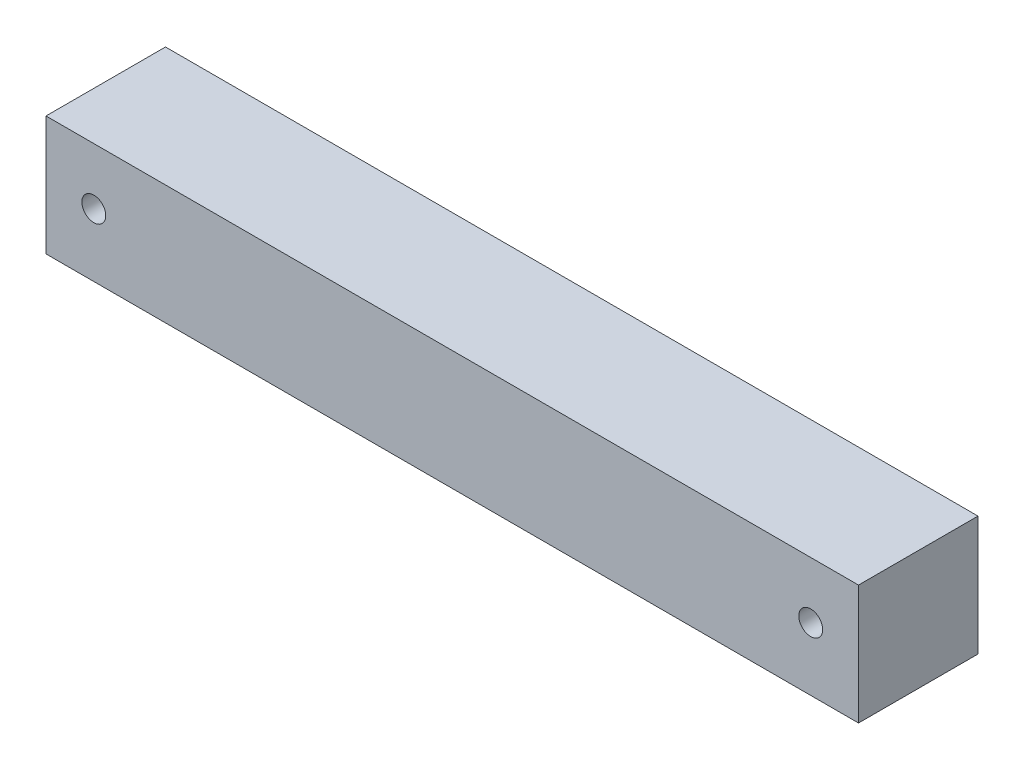
SolidWorks part; units mm, degrees
ref_plane "Plan de face" through (0, 0, 0) normal (0, 0, 1) x (1, 0, 0)
ref_plane "Plan de dessus" through (0, 0, 0) normal (0, 1, 0) x (1, 0, 0)
ref_plane "Plan de droite" through (0, 0, 0) normal (1, 0, 0) x (0, 0, -1)
sketch "Esquisse1" plane through (0, 0, 0) normal (0, 0, 1) x (1, 0, 0)
  line L1 (-19.0581, 21.2859) -> (48.9419, 21.2859)
  line L2 (-19.0581, 21.2859) -> (-19.0581, 11.2859)
  line L3 (-19.0581, 11.2859) -> (48.9419, 11.2859)
  line L4 (48.9419, 21.2859) -> (48.9419, 11.2859)
  circle A0 centre (44.9419, 16.5536) radius 1
  circle A1 centre (-15.0581, 16.5536) radius 1
  dimension "D3" = 2
  dimension "D4" = 2
  dimension "D1" = 60
  dimension "D2" = 10
  dimension "D5" = 4
  dimension "D6" = 4
extrude "Boss.-Extru.1" add sketch "Esquisse1" along normal blind 10
